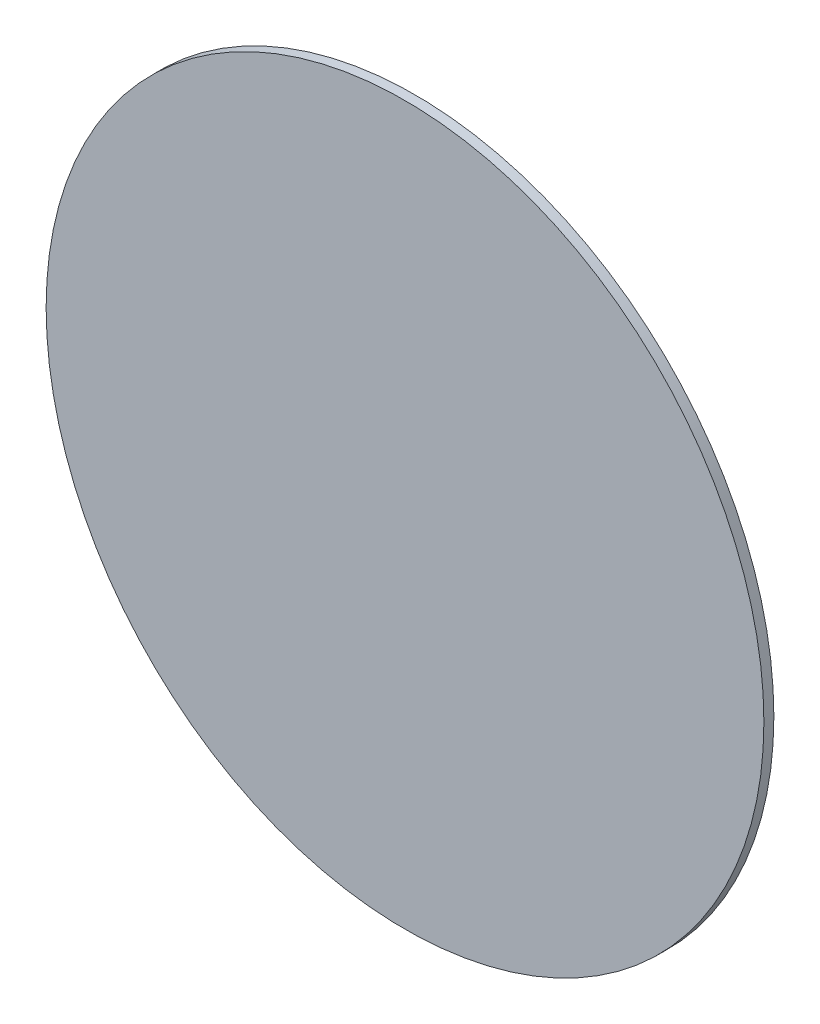
SolidWorks part; units mm, degrees
ref_plane "Спереди" through (0, 0, 0) normal (0, 0, 1) x (1, 0, 0)
ref_plane "Сверху" through (0, 0, 0) normal (0, 1, 0) x (1, 0, 0)
ref_plane "Справа" through (0, 0, 0) normal (1, 0, 0) x (0, 0, -1)
sketch "Эскиз1" plane through (0, 0, 0) normal (0, 0, 1) x (1, 0, 0)
  circle A0 centre (0, 0) radius 360
  dimension "D1" = 720
extrude "Бобышка-Вытянуть1" add sketch "Эскиз1" along normal blind 10
